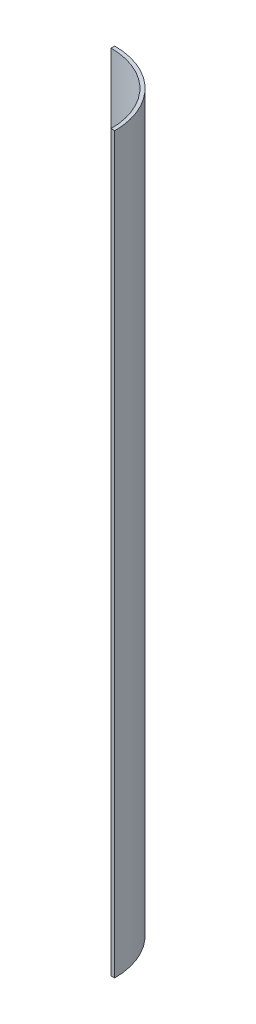
SolidWorks part; units mm, degrees
ref_plane "Front Plane" through (0, 0, 0) normal (0, 0, 1) x (1, 0, 0)
ref_plane "Top Plane" through (0, 0, 0) normal (0, 1, 0) x (1, 0, 0)
ref_plane "Right Plane" through (0, 0, 0) normal (1, 0, 0) x (0, 0, -1)
sketch "Sketch1" plane through (0, 0, 0) normal (0, 1, 0) x (1, 0, 0)
  line L0 (0, 24.13) -> (0, 25.4)
  line L1 (24.13, 0) -> (25.4, 0)
  line L2 (0, 0) -> (0, 25.4) construction
  line L3 (0, 0) -> (25.4, 0) construction
  arc A0 (0, 25.4) -> (25.4, 0) centre (0, 0) cw
  arc A1 (0, 24.13) -> (24.13, 0) centre (0, 0) cw
  dimension "D2" = 25.4
  dimension "D3" = 24.13
  dimension "D1" = 90
extrude "Boss-Extrude2" add sketch "Sketch1" along normal blind 254
